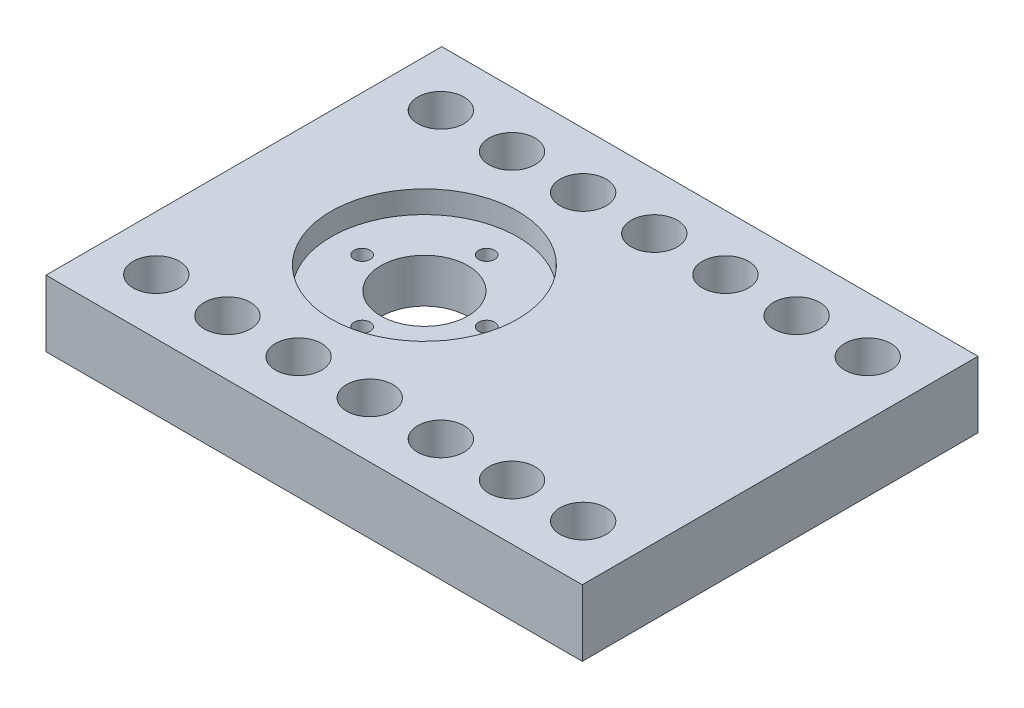
SolidWorks part; units mm, degrees
ref_plane "Front Plane" through (0, 0, 0) normal (0, 0, 1) x (1, 0, 0)
ref_plane "Top Plane" through (0, 0, 0) normal (0, 1, 0) x (1, 0, 0)
ref_plane "Right Plane" through (0, 0, 0) normal (1, 0, 0) x (0, 0, -1)
sketch "Sketch3" plane through (0, 0, 0) normal (0, 1, 0) x (1, 0, 0)
  line L0 (-52.2632, 0) -> (55.5227, 0) construction
  line L1 (0, 43.998) -> (0, -43.557) construction
  line L2 (-9.85, 40.6896) -> (-9.85, -33.1895) construction
  circle A0 centre (-9.85, 0) radius 10 construction
  circle A1 centre (-9.85, 0) radius 7 construction
  circle A2 centre (-9.85, 7) radius 0.9
  circle A3 centre (-16.85, 0) radius 0.9
  circle A4 centre (-9.85, -7) radius 0.9
  circle A5 centre (-2.85, 0) radius 0.9
  circle A6 centre (-9.85, 0) radius 4.9
  line B0 (-34.3973, 0) -> (32.9918, 0) construction
  line B1 (-20.15, 9.75) -> (-20.15, -9.75) construction
  line B2 (20.15, 9.75) -> (20.15, -9.75) construction
  line B3 (-20.15, 9.75) -> (20.15, -9.75) construction
  line B4 (-20.15, -9.75) -> (20.15, 9.75) construction
  line B5 (0, 26.5192) -> (0, -28.2205) construction
  line B6 (-30.15, 22.25) -> (30.15, 22.25)
  line B7 (-30.15, 22.25) -> (-30.15, -22.25)
  line B8 (-30.15, -22.25) -> (30.15, -22.25)
  line B9 (30.15, 22.25) -> (30.15, -22.25)
  line B10 (-27, 9.75) -> (27, 9.75) construction
  line B11 (-27, 9.75) -> (-27, -9.75) construction
  line B12 (-27, -9.75) -> (27, -9.75) construction
  line B13 (27, 9.75) -> (27, -9.75) construction
  line B14 (-27, 9.75) -> (27, -9.75) construction
  line B15 (-27, -9.75) -> (27, 9.75) construction
  dimension "D8" = 1.8
  dimension "D4" = 20
  dimension "D5" = 14
  dimension "D6" = 1.8
  dimension "D7" = 1.8
  dimension "D9" = 1.8
  dimension "D10" = 9.8
  dimension "D1" = 0
  dimension "D2" = 0
  dimension "D3" = 9.85
sketch_block_instance "Block3-1"
sketch_block "Block3" parameters "D1"=40.3, "D2"=19.5, "D3"=10, "D4"=10, "D5"=54, "D6"=34.5, "D7"=17.25
extrude "Boss-Extrude1" add sketch "Sketch3" along normal blind 7.46
sketch "Sketch4" plane through (0, 7.46, 0) normal (0, 1, 0) x (1, 0, 0)
  line L0 (0, 22.25) -> (0, -22.25) construction
  line L1 (30.15, 22.25) -> (-30.15, 22.25) construction
  line L2 (-30.15, -22.25) -> (30.15, -22.25) construction
  line L3 (-30.15, 0) -> (30.15, 0) construction
  line L4 (-30.15, 22.25) -> (-30.15, -22.25) construction
  line L5 (30.15, -22.25) -> (30.15, 22.25) construction
  line L6 (-9.85, 7) -> (-9.85, -7) construction
  circle A0 centre (-9.85, 0) radius 10.5
  dimension "D1" = 21
extrude "Cut-Extrude1" cut sketch "Sketch4" against normal blind 2.5
sketch "Sketch5" plane through (0, 7.46, 0) normal (0, 1, 0) x (1, 0, 0)
  line L0 (-30.15, 16) -> (30.15, 16) construction
  line L1 (-30.15, 22.25) -> (-30.15, -22.25) construction
  line L2 (30.15, -22.25) -> (30.15, 22.25) construction
  line L3 (30.15, 22.25) -> (-30.15, 22.25) construction
  line L4 (-30.15, -16) -> (30.15, -16) construction
  line L5 (-30.15, -22.25) -> (30.15, -22.25) construction
  line L6 (0, 22.25) -> (0, -22.25) construction
  line L7 (-30.15, 0) -> (30.15, 0) construction
  circle A0 centre (0, 16) radius 2.6
  circle A1 centre (8, 16) radius 2.6
  circle A2 centre (16, 16) radius 2.6
  circle A3 centre (24, 16) radius 2.6
  circle A4 centre (-24, 16) radius 2.6
  circle A5 centre (-16, 16) radius 2.6
  circle A6 centre (-8, 16) radius 2.6
  circle A7 centre (-8, -16) radius 2.6
  circle A8 centre (-16, -16) radius 2.6
  circle A9 centre (-24, -16) radius 2.6
  circle A10 centre (24, -16) radius 2.6
  circle A11 centre (16, -16) radius 2.6
  circle A12 centre (8, -16) radius 2.6
  circle A13 centre (0, -16) radius 2.6
  dimension "D3" = 5.2
  dimension "D5" = 8
  dimension "D1" = 6.25
  dimension "D2" = 6.25
  dimension "D4" = 4
extrude "Cut-Extrude2" cut sketch "Sketch5" against normal through all
